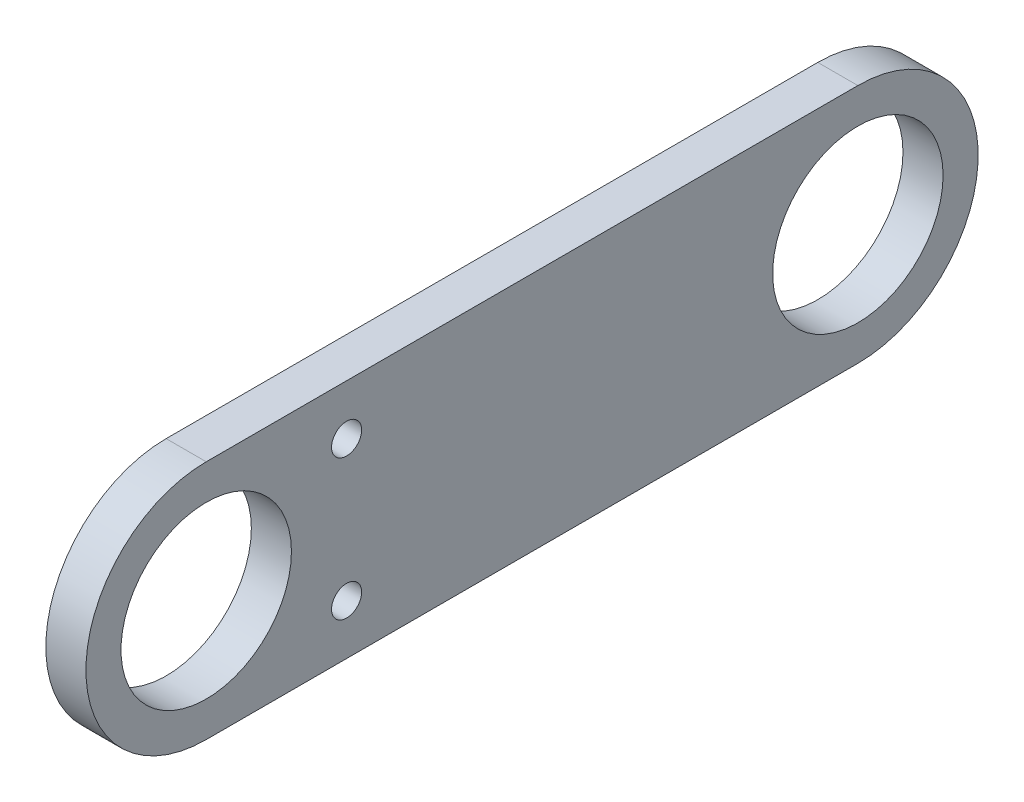
SolidWorks part; units mm, degrees
ref_plane "前视基准面" through (0, 0, 0) normal (0, 0, 1) x (1, 0, 0)
ref_plane "上视基准面" through (0, 0, 0) normal (0, 1, 0) x (1, 0, 0)
ref_plane "右视基准面" through (0, 0, 0) normal (1, 0, 0) x (0, 0, -1)
sketch "草图1" plane through (0, 0, 0) normal (1, 0, 0) x (0, 0, -1)
  line L0 (0, 0) -> (56, 0) construction
  line L1 (56, 0) -> (56, 12) construction
  line L2 (-9, 12) -> (0, 12)
  line L3 (0, -12) -> (56, -12)
  line L4 (0, 12) -> (56, 12)
  line L5 (0, -12) -> (-9, -12)
  line L6 (0, 12) -> (5, 7)
  line L7 (0, 0) -> (-9, 0) construction
  circle A0 centre (56, 0) radius 8.5
  arc A1 (56, 12) -> (56, -12) centre (56, 0) cw
  circle A2 centre (5, 7) radius 1.5
  circle A3 centre (5, -7) radius 1.5
  circle A4 centre (-9, 0) radius 8.5
  arc A5 (-9, 12) -> (-9, -12) centre (-9, 0) ccw
  dimension "D2" = 12
  dimension "D5" = 2
  dimension "D8" = 17
  dimension "D1" = 56
  dimension "D3" = 5
  dimension "D4" = 5
  dimension "D6" = 9
extrude "凸台-拉伸1" add sketch "草图1" along normal blind 4
